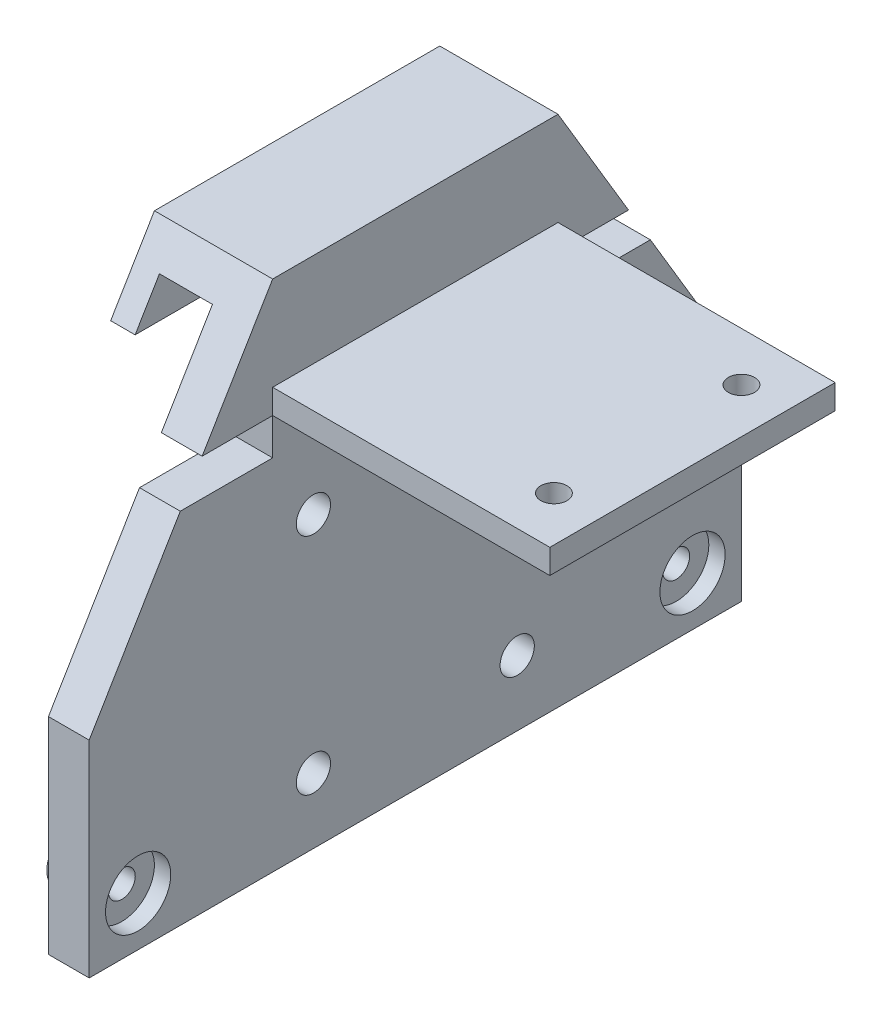
SolidWorks part; units mm, degrees
ref_plane "前视基准面" through (0, 0, 0) normal (0, 0, 1) x (1, 0, 0)
ref_plane "上视基准面" through (0, 0, 0) normal (0, 1, 0) x (1, 0, 0)
ref_plane "右视基准面" through (0, 0, 0) normal (1, 0, 0) x (0, 0, -1)
sketch "草图1" plane through (0, 0, 0) normal (1, 0, 0) x (0, 0, -1)
  line L1 (-40, 31.5) -> (40, 31.5)
  line L2 (-40, 31.5) -> (-40, -31.5)
  line L3 (-40, -31.5) -> (40, -31.5)
  line L4 (40, 31.5) -> (40, -31.5)
  line L5 (-40, 31.5) -> (40, -31.5) construction
  line L6 (-40, -31.5) -> (40, 31.5) construction
  line L7 (-40, -31.5) -> (40, -31.5) construction
  line L8 (-40, -31.5) -> (-40, -25.5) construction
  line L9 (-40, -25.5) -> (40, -25.5) construction
  line L10 (40, -31.5) -> (40, -25.5) construction
  line L11 (-40, -31.5) -> (40, -25.5) construction
  line L12 (-40, -25.5) -> (40, -31.5) construction
  line L13 (-34, -25.5) -> (34, -25.5) construction
  line L14 (-34, -25.5) -> (-34, -31.5) construction
  line L15 (-34, -31.5) -> (34, -31.5) construction
  line L16 (34, -25.5) -> (34, -31.5) construction
  line L17 (-34, -25.5) -> (34, -31.5) construction
  line L18 (-34, -31.5) -> (34, -25.5) construction
  circle A0 centre (-34, -25.5) radius 1.65
  circle A1 centre (34, -25.5) radius 1.65
  point P0 (0, 0)
  point P8 (0, -28.5)
  point P9 (0, -28.5)
  dimension "D3" = 63
  dimension "D1" = 6
  dimension "D2" = 68
extrude "凸台-拉伸1" add sketch "草图1" along normal blind 10
sketch "草图2" plane through (10, 0, 0) normal (1, 0, 0) x (0, 0, -1)
  circle A0 centre (-34, -25.5) radius 4
  circle A1 centre (34, -25.5) radius 4
extrude "切除-拉伸1" cut sketch "草图2" against normal offset from surface (7 mm away) 3 up to face at (0, 0, 0)
sketch "草图3" plane through (10, 0, 0) normal (1, 0, 0) x (0, 0, -1)
  line L1 (-40, 31.5) -> (40, 31.5)
  line L2 (-40, 31.5) -> (-40, -31.5)
  line L3 (-40, -31.5) -> (40, -31.5)
  line L4 (40, 31.5) -> (40, -31.5)
  line L5 (-40, 31.5) -> (40, -31.5) construction
  line L6 (-40, -31.5) -> (40, 31.5) construction
  point P4 (0, 0)
extrude "切除-拉伸2" cut sketch "草图3" against normal blind 5
sketch "草图4" plane through (0, 0, 0) normal (-1, 0, 0) x (0, 0, 1)
  circle A0 centre (-34, -25.5) radius 3.2
  circle A1 centre (34, -25.5) radius 3.2
  circle A2 centre (-34, -25.5) radius 1.65
  circle A3 centre (34, -25.5) radius 1.65
extrude "凸台-拉伸2" add sketch "草图4" along normal blind 3
sketch "草图5" plane through (0, 0, 40) normal (0, 0, 1) x (1, 0, 0)
  line L0 (-6.5, 27.5) -> (-6.5, 22.5)
  line L1 (0, 31.5) -> (-6.5, 31.5)
  line L2 (0, 31.5) -> (0, 27.5)
  line L3 (0, 27.5) -> (-6.5, 27.5)
  line L5 (0, 31.5) -> (-6.5, 27.5) construction
  line L6 (0, 27.5) -> (-6.5, 31.5) construction
  line L7 (-6.5, 31.5) -> (-9.5, 31.5)
  line L9 (-6.5, 22.5) -> (-9.5, 22.5)
  line L10 (-9.5, 31.5) -> (-9.5, 22.5)
  line L11 (-6.5, 31.5) -> (-9.5, 22.5) construction
  line L12 (-6.5, 22.5) -> (-9.5, 31.5) construction
  point P4 (-3.25, 29.5)
  point P9 (-8, 27)
  dimension "D1" = 4
  dimension "D2" = 6.5
  dimension "D3" = 5
  dimension "D4" = 3
extrude "凸台-拉伸3" add sketch "草图5" against normal up to surface (80 mm away) up to face at (2.5, 0, -40)
sketch "草图6" plane through (5, 0, 0) normal (1, 0, 0) x (0, 0, -1)
  line L0 (40, -31.5) -> (40, 31.5) construction
  line L1 (-40, 31.5) -> (40, 31.5) construction
  line L2 (-40, 31.5) -> (-40, -6.2315) construction
  line L3 (-40, -6.2315) -> (40, -6.2315) construction
  line L4 (40, 31.5) -> (40, -6.2315) construction
  line L5 (-40, 31.5) -> (40, -6.2315) construction
  line L6 (-40, -6.2315) -> (40, 31.5) construction
  line L7 (-17.5, 31.5) -> (-40, -6.2315)
  line L8 (-17.5, 31.5) -> (17.5, 31.5) construction
  line L9 (-17.5, 31.5) -> (-17.5, -6.2315) construction
  line L10 (-17.5, -6.2315) -> (17.5, -6.2315) construction
  line L11 (17.5, 31.5) -> (17.5, -6.2315) construction
  line L12 (-17.5, 31.5) -> (17.5, -6.2315) construction
  line L13 (-17.5, -6.2315) -> (17.5, 31.5) construction
  line L14 (-40, -6.2315) -> (-40, 31.5)
  line L15 (-40, 31.5) -> (-17.5, 31.5)
  line L16 (17.5, 31.5) -> (40, 31.5)
  line L17 (40, 31.5) -> (40, -6.2315)
  line L18 (40, -6.2315) -> (17.5, 31.5)
  point P4 (0, 12.6343)
  point P8 (0, 12.6343)
  dimension "D1" = 35
extrude "切除-拉伸3" cut sketch "草图6" against normal through all
sketch "草图7" plane through (5, 0, 0) normal (1, 0, 0) x (0, 0, -1)
  line L0 (-34, -25.5) -> (34, -25.5) construction
  line L1 (-12.5, 4) -> (12.5, 4) construction
  line L2 (-34, -25.5) -> (34, -25.5) construction
  line L3 (-34, -25.5) -> (-34, 4) construction
  line L4 (-34, 4) -> (34, 4) construction
  line L5 (34, -25.5) -> (34, 4) construction
  line L6 (0, 4) -> (0, -25.5) construction
  line L7 (-34, -10.75) -> (34, -10.75) construction
  circle A0 centre (-12.5, 4) radius 2.1
  circle A1 centre (12.5, 4) radius 2.1
  point P8 (0, 4)
  point P332 (0, -10.75)
  dimension "D1" = 29.5
  dimension "D2" = 25
extrude "切除-拉伸4" cut sketch "草图7" against normal through all
sketch "草图8" plane through (0, 0, 0) normal (-1, 0, 0) x (0, 0, 1)
  line L0 (-34, -25.5) -> (34, -25.5) construction
  line L2 (-34, -25.5) -> (34, -25.5) construction
  line L3 (-34, -25.5) -> (-34, -23.5) construction
  line L4 (-34, -23.5) -> (34, -23.5) construction
  line L5 (34, -25.5) -> (34, -23.5) construction
  line L6 (0, -23.5) -> (0, -25.5) construction
  line L7 (-34, -24.5) -> (34, -24.5) construction
  line L8 (-12.5, -25.5) -> (12.5, -25.5) construction
  line L9 (-12.5, -25.5) -> (-12.5, -23.5) construction
  line L10 (-12.5, -23.5) -> (12.5, -23.5) construction
  line L11 (12.5, -25.5) -> (12.5, -23.5) construction
  line L12 (-12.5, -25.5) -> (12.5, -23.5) construction
  line L13 (-12.5, -23.5) -> (12.5, -25.5) construction
  circle A0 centre (-12.5, -23.5) radius 2.1
  circle A1 centre (12.5, -23.5) radius 2.1
  point P7 (0, -24.5)
  point P166 (0, -24.5)
  dimension "D1" = 2
  dimension "D2" = 25
extrude "切除-拉伸5" cut sketch "草图8" against normal through all
sketch "草图9" plane through (5, 0, 0) normal (1, 0, 0) x (0, 0, -1)
  line L0 (-17.5, 31.5) -> (17.5, 31.5) construction
  line L1 (17.5, 12.5) -> (34.6965, 12.5)
  line L2 (-17.5, 31.5) -> (17.5, 31.5) construction
  line L3 (-17.5, 31.5) -> (-17.5, 17) construction
  line L4 (-17.5, 17) -> (17.5, 17) construction
  line L5 (17.5, 31.5) -> (17.5, 17) construction
  line L6 (0, 17) -> (0, 31.5) construction
  line L7 (-17.5, 24.25) -> (17.5, 24.25) construction
  line L8 (-17.5, 17) -> (-34.6965, 17)
  line L9 (-17.5, 17) -> (-17.5, 12.5)
  line L10 (-17.5, 12.5) -> (-34.6965, 12.5)
  line L11 (-34.6965, 17) -> (-34.6965, 12.5)
  line L12 (-26.0983, 12.5) -> (-26.0983, 17) construction
  line L13 (-17.5, 14.75) -> (-34.6965, 14.75) construction
  line L14 (34.6965, 17) -> (34.6965, 12.5)
  line L15 (17.5, 17) -> (34.6965, 17)
  line L16 (17.5, 17) -> (17.5, 12.5)
  point P216 (0, 24.25)
  point P512 (-26.0983, 14.75)
  dimension "D1" = 14.5
  dimension "D2" = 4.5
extrude "切除-拉伸6" cut sketch "草图9" against normal up to next
sketch "草图10" plane through (5, 0, 0) normal (1, 0, 0) x (0, 0, -1)
  line L0 (-17.5, 31.5) -> (17.5, 31.5) construction
  line L2 (-17.5, 31.5) -> (17.5, 31.5) construction
  line L3 (-17.5, 31.5) -> (-17.5, 17) construction
  line L4 (-17.5, 17) -> (17.5, 17) construction
  line L5 (17.5, 31.5) -> (17.5, 17) construction
  line L6 (0, 17) -> (0, 31.5) construction
  line L7 (-17.5, 24.25) -> (17.5, 24.25) construction
  line L8 (-17.5, 17) -> (17.5, 17)
  line L9 (-17.5, 17) -> (-17.5, 20)
  line L10 (-17.5, 20) -> (17.5, 20)
  line L11 (17.5, 17) -> (17.5, 20)
  line L12 (0, 20) -> (0, 17) construction
  line L13 (-17.5, 18.5) -> (17.5, 18.5) construction
  point P141 (0, 18.5)
  point P162 (0, 24.25)
  dimension "D1" = 3
extrude "凸台-拉伸4" add sketch "草图10" along normal blind 34
sketch "草图11" plane through (0, 20, 0) normal (0, 1, 0) x (1, 0, 0)
  line L0 (39, -17.5) -> (5, -17.5) construction
  line L1 (39, 17.5) -> (19, 17.5) construction
  line L2 (39, 17.5) -> (39, -17.5) construction
  line L3 (39, -17.5) -> (19, -17.5) construction
  line L4 (19, 17.5) -> (19, -17.5) construction
  line L5 (29, -17.5) -> (29, 17.5) construction
  line L6 (39, 0) -> (19, 0) construction
  line L8 (24.5, 11.5) -> (33.5, 11.5) construction
  line L9 (24.5, 11.5) -> (24.5, -11.5) construction
  line L10 (24.5, -11.5) -> (33.5, -11.5) construction
  line L11 (33.5, 11.5) -> (33.5, -11.5) construction
  line L12 (29, -11.5) -> (29, 11.5) construction
  line L13 (24.5, 0) -> (33.5, 0) construction
  circle A0 centre (33.5, 11.5) radius 1.6
  circle A1 centre (33.5, -11.5) radius 1.6
  point P6 (29, 0)
  point P184 (29, 0)
  dimension "D1" = 23
  dimension "D2" = 20
  dimension "D3" = 9
extrude "切除-拉伸7" cut sketch "草图11" against normal through all
